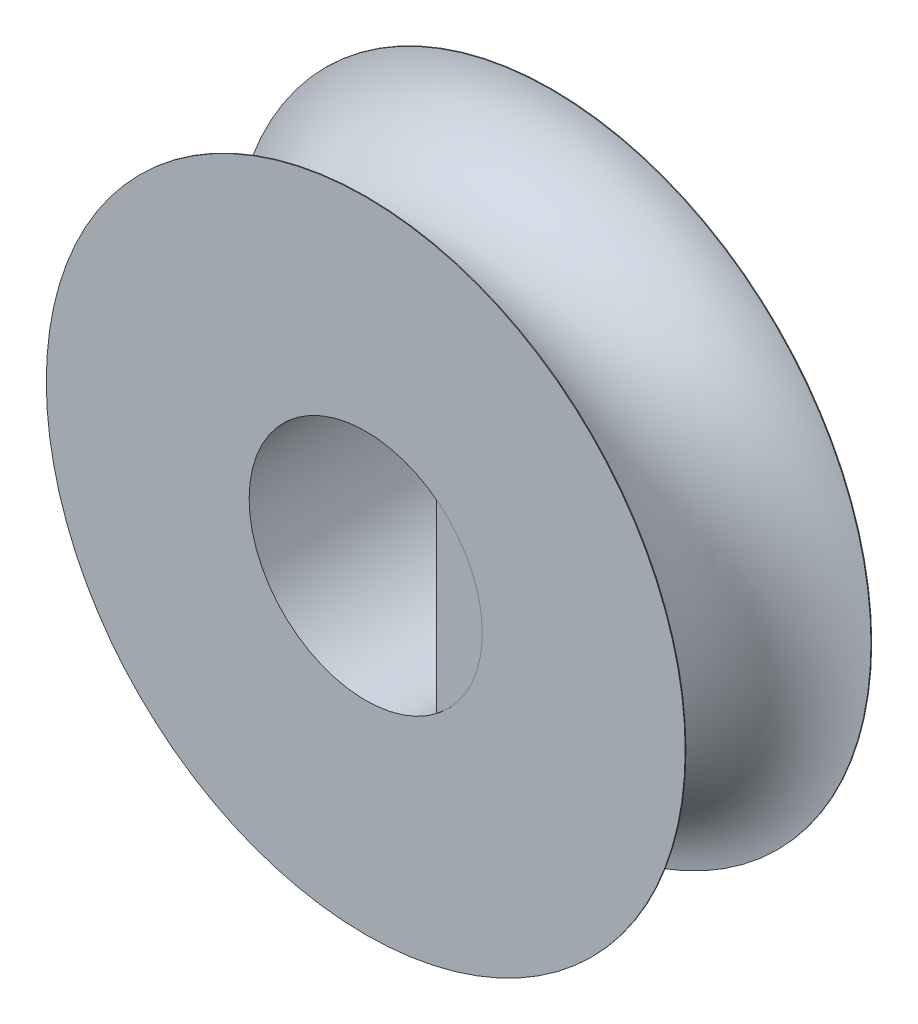
SolidWorks part; units mm, degrees
material "사용자정의 플라스틱"
ref_plane "정면" through (0, 0, 0) normal (0, 0, 1) x (1, 0, 0)
ref_plane "윗면" through (0, 0, 0) normal (0, 1, 0) x (1, 0, 0)
ref_plane "우측면" through (0, 0, 0) normal (1, 0, 0) x (0, 0, -1)
sketch "스케치1" plane through (0, 0, 0) normal (0, 0, 1) x (1, 0, 0)
  circle A0 centre (0, 0) radius 13.7
  dimension "D1" = 27.4
extrude "보스-돌출1" add sketch "스케치1" along normal blind 8
sketch "스케치2" plane through (0, 0, 0) normal (0, 1, 0) x (1, 0, 0)
  line L0 (-14.7, 0) -> (-14.7, -8)
  line L1 (-14.7, -8) -> (-14.2, -8)
  line L2 (-14.7, 0) -> (-14.2, 0)
  line L3 (-13.7, -8) -> (13.7, -8) construction
  line L4 (0, -12.5866) -> (0, 4.0867) construction
  arc A0 (-14.2, 0) -> (-14.2, -8) centre (-14.2, -4) cw
  dimension "D1" = 14.7
  dimension "D2" = 8
  dimension "D3" = 0
  dimension "D4" = 0.5
revolve "컷-회전1" cut sketch "스케치2" angle 360 about L4
sketch "스케치4" plane through (0, 0, 0) normal (0, 0, -1) x (-1, 0, 0)
  circle A0 centre (0, 0) radius 5
  dimension "D1" = 10
extrude "컷-돌출1" cut sketch "스케치4" against normal through all
ref_plane "평면2" through (3, 0, 0) normal (1, 0, 0) x (0, 0, -1)
sketch "스케치5" plane through (3, 0, 0) normal (1, 0, 0) x (0, 0, -1)
  line L0 (-7.9686, 13.7) -> (-7.9686, -13.7) construction
  line L1 (-7.9686, 6.6986) -> (0, 6.6986)
  line L2 (-7.9686, 6.6986) -> (-7.9686, -6.8537)
  line L3 (-7.9686, -6.8537) -> (0, -6.8537)
  line L4 (0, 6.6986) -> (0, -6.8537)
  line L5 (0, -13.7) -> (0, 13.7) construction
extrude "보스-돌출2" add sketch "스케치5" along normal up to surface up to face at (-5, 0, 8)
